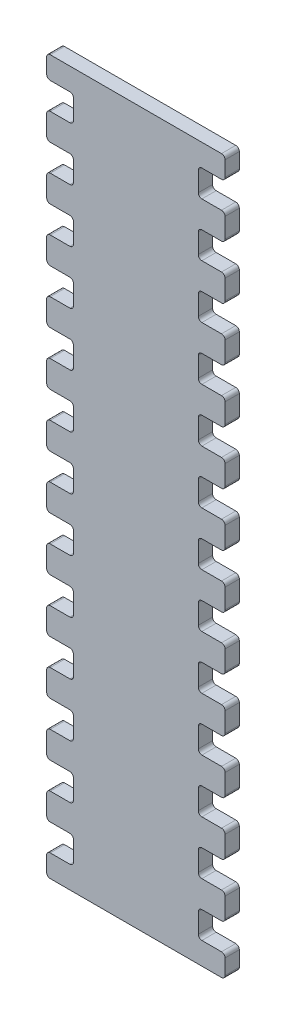
SolidWorks part; units mm, degrees
ref_plane "Front Plane" through (0, 0, 0) normal (0, 0, 1) x (1, 0, 0)
ref_plane "Top Plane" through (0, 0, 0) normal (0, 1, 0) x (1, 0, 0)
ref_plane "Right Plane" through (0, 0, 0) normal (1, 0, 0) x (0, 0, -1)
sketch "Sketch1" plane through (0, 0, 0) normal (0, 0, 1) x (1, 0, 0)
  line L1 (-100, 0) -> (100, 0)
  line L2 (-100, 0) -> (-100, 800)
  line L3 (-100, 800) -> (100, 800)
  line L4 (100, 0) -> (100, 800)
  point P4 (0, 0)
  dimension "D1" = 200
  dimension "D2" = 800
extrude "Boss-Extrude1" add sketch "Sketch1" along normal blind 16
sketch "Sketch2" plane through (0, 0, 16) normal (0, 0, 1) x (1, 0, 0)
  line L0 (100, 0) -> (100, 25)
  line L1 (100, 0) -> (100, 800) construction
  line L2 (100, 25) -> (70, 25)
  line L3 (70, 25) -> (70, 55)
  line L4 (70, 55) -> (100, 55)
  line L5 (70, 110) -> (100, 110)
  line L6 (70, 80) -> (70, 110)
  line L7 (100, 80) -> (70, 80)
  line L8 (100, 55) -> (100, 80)
  line L9 (70, 165) -> (100, 165)
  line L10 (70, 135) -> (70, 165)
  line L11 (100, 135) -> (70, 135)
  line L12 (100, 110) -> (100, 135)
  line L13 (70, 220) -> (100, 220)
  line L14 (70, 190) -> (70, 220)
  line L15 (100, 190) -> (70, 190)
  line L16 (100, 165) -> (100, 190)
  line L17 (70, 275) -> (100, 275)
  line L18 (70, 245) -> (70, 275)
  line L19 (100, 245) -> (70, 245)
  line L20 (100, 220) -> (100, 245)
  line L21 (70, 330) -> (100, 330)
  line L22 (70, 300) -> (70, 330)
  line L23 (100, 300) -> (70, 300)
  line L24 (100, 275) -> (100, 300)
  line L25 (70, 385) -> (100, 385)
  line L26 (70, 355) -> (70, 385)
  line L27 (100, 355) -> (70, 355)
  line L28 (100, 330) -> (100, 355)
  line L29 (70, 440) -> (100, 440)
  line L30 (70, 410) -> (70, 440)
  line L31 (100, 410) -> (70, 410)
  line L32 (100, 385) -> (100, 410)
  line L33 (70, 495) -> (100, 495)
  line L34 (70, 465) -> (70, 495)
  line L35 (100, 465) -> (70, 465)
  line L36 (100, 440) -> (100, 465)
  line L37 (70, 550) -> (100, 550)
  line L38 (70, 520) -> (70, 550)
  line L39 (100, 520) -> (70, 520)
  line L40 (100, 495) -> (100, 520)
  line L41 (70, 605) -> (100, 605)
  line L42 (70, 575) -> (70, 605)
  line L43 (100, 575) -> (70, 575)
  line L44 (100, 550) -> (100, 575)
  line L45 (70, 660) -> (100, 660)
  line L46 (70, 630) -> (70, 660)
  line L47 (100, 630) -> (70, 630)
  line L48 (100, 605) -> (100, 630)
  line L49 (70, 715) -> (100, 715)
  line L50 (70, 685) -> (70, 715)
  line L51 (100, 685) -> (70, 685)
  line L52 (100, 660) -> (100, 685)
  line M3 (100, 0) -> (100, 800)
  dimension "D1" = 25
  dimension "D2" = 30
  dimension "D3" = 30
  dimension "D4" = 13
extrude "Cut-Extrude8" cut sketch "Sketch2" against normal through all both and the other way through all contours L4 L3 L2 M3
pattern_linear "LPattern1" count 13 spacing 60 along (0, 1, 0) of "Cut-Extrude8"
sketch "Sketch3" plane through (0, 0, 16) normal (0, 0, 1) x (1, 0, 0)
  line L0 (0, 0) -> (0, 800) construction
  line L1 (100, 800) -> (-100, 800) construction
ref_plane "Plane1" through (0, 0, 0) normal (1, 0, 0) x (0, 0, -1)
mirror "Mirror1" about plane through (0, 0, 0) normal (1, 0, 0) of "Cut-Extrude8"
mirror "Mirror2" about plane through (0, 0, 0) normal (1, 0, 0) of "LPattern1"
fillet "Fillet2" radius 4 108 edges at (-70, 115, 8) (-70, 85, 8) (-100, 85, 8) (-100, 55, 8) (-70, 55, 8) (-70, 25, 8) (-100, 25, 8) (-100, 0, 8) (100, 0, 8) (100, 25, 8) (70, 55, 8) (100, 55, 8) (100, 85, 8) (70, 85, 8) (70, 115, 8) (100, 115, 8) (100, 145, 8) (70, 145, 8) (70, 175, 8) (100, 175, 8) (100, 205, 8) (70, 205, 8) (70, 235, 8) (100, 235, 8) (100, 265, 8) (70, 265, 8) (70, 295, 8) (100, 295, 8) (100, 325, 8) (70, 325, 8) (70, 355, 8) (100, 355, 8) (100, 385, 8) (70, 385, 8) (70, 415, 8) (100, 415, 8) (100, 445, 8) (70, 445, 8) (70, 475, 8) (100, 475, 8) (100, 505, 8) (70, 505, 8) (70, 535, 8) (100, 535, 8) (100, 565, 8) (70, 565, 8) (70, 595, 8) (100, 595, 8) (100, 625, 8) (70, 625, 8) (70, 655, 8) (100, 655, 8) (100, 685, 8) (70, 685, 8) (70, 715, 8) (100, 715, 8) (100, 745, 8) (70, 745, 8) (70, 775, 8) (100, 775, 8) (100, 800, 8) (-100, 800, 8) (-100, 775, 8) (-70, 775, 8) (-70, 745, 8) (-100, 745, 8) (-100, 715, 8) (-70, 715, 8) (-70, 685, 8) (-100, 685, 8) (-100, 655, 8) (-70, 655, 8) (-70, 625, 8) (-100, 625, 8) (-100, 595, 8) (-70, 595, 8) (-70, 565, 8) (-100, 565, 8) (-100, 535, 8) (-70, 535, 8) (-70, 505, 8) (-100, 505, 8) (-100, 475, 8) (-70, 475, 8) (-70, 445, 8) (-100, 445, 8) (-100, 415, 8) (-70, 415, 8) (-70, 385, 8) (-100, 385, 8) (-100, 355, 8) (-70, 355, 8) (-70, 325, 8) (-100, 325, 8) (-100, 295, 8) (-70, 295, 8) (-70, 265, 8) (-100, 265, 8) (-100, 235, 8) (-70, 235, 8) (-70, 205, 8) (-100, 205, 8) (-100, 175, 8) (-70, 175, 8) (-70, 145, 8) (-100, 145, 8) (-100, 115, 8) (70, 25, 8)
